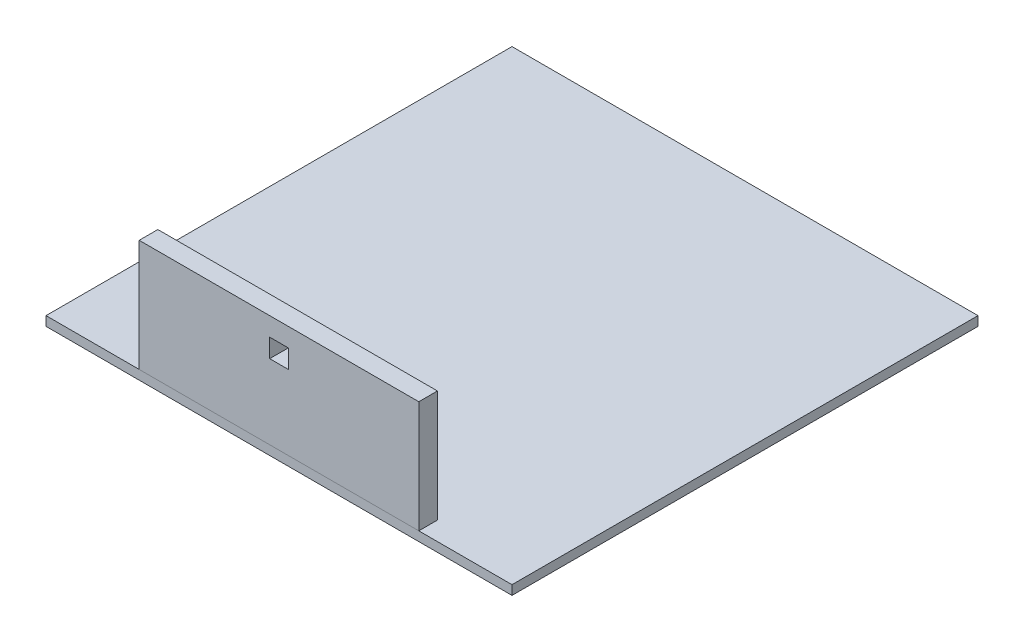
SolidWorks part; units mm, degrees
material "Teak"
ref_plane "Front Plane" through (0, 0, 0) normal (0, 0, 1) x (1, 0, 0)
ref_plane "Top Plane" through (0, 0, 0) normal (0, 1, 0) x (1, 0, 0)
ref_plane "Right Plane" through (0, 0, 0) normal (1, 0, 0) x (0, 0, -1)
sketch "Sketch1" plane through (0, 0, 0) normal (0, 1, 0) x (1, 0, 0)
  line L1 (-250, -250) -> (250, -250)
  line L2 (-250, -250) -> (-250, 250)
  line L3 (-250, 250) -> (250, 250)
  line L4 (250, -250) -> (250, 250)
  line L5 (-250, -250) -> (250, 250) construction
  line L6 (-250, 250) -> (250, -250) construction
  point P0 (0, 0)
  dimension "D1" = 500
  dimension "D2" = 500
extrude "Boss-Extrude1" add sketch "Sketch1" along normal blind 10
sketch "Sketch5" plane through (0, 10, 0) normal (0, 1, 0) x (1, 0, 0)
  line L0 (-250, -250) -> (250, -250) construction
  line L1 (-150, -230) -> (150, -230)
  line L2 (-150, -230) -> (-150, -250)
  line L3 (-150, -250) -> (150, -250)
  line L4 (150, -230) -> (150, -250)
  line L5 (-150, -230) -> (150, -250) construction
  line L6 (-150, -250) -> (150, -230) construction
  line L7 (250, -250) -> (250, 250) construction
  point P0 (0, -240)
  dimension "D1" = 300
  dimension "D2" = 20
  dimension "D3" = 0
  dimension "D4" = 100
extrude "Boss-Extrude4" add sketch "Sketch5" along normal blind 120 separate body
sketch "Sketch7" plane through (0, 0, 250) normal (0, 0, 1) x (1, 0, 0)
  line L0 (150, 130) -> (150, 10) construction
  line L1 (-10, 90) -> (10, 90)
  line L2 (-10, 90) -> (-10, 110)
  line L3 (-10, 110) -> (10, 110)
  line L4 (10, 90) -> (10, 110)
  line L5 (-10, 90) -> (10, 110) construction
  line L6 (-10, 110) -> (10, 90) construction
  line L9 (-150, 130) -> (150, 130) construction
  point P0 (0, 100)
  dimension "D1" = 20
  dimension "D2" = 20
  dimension "D3" = 150
  dimension "D4" = 20
extrude "Cut-Extrude1" cut sketch "Sketch7" against normal through all
